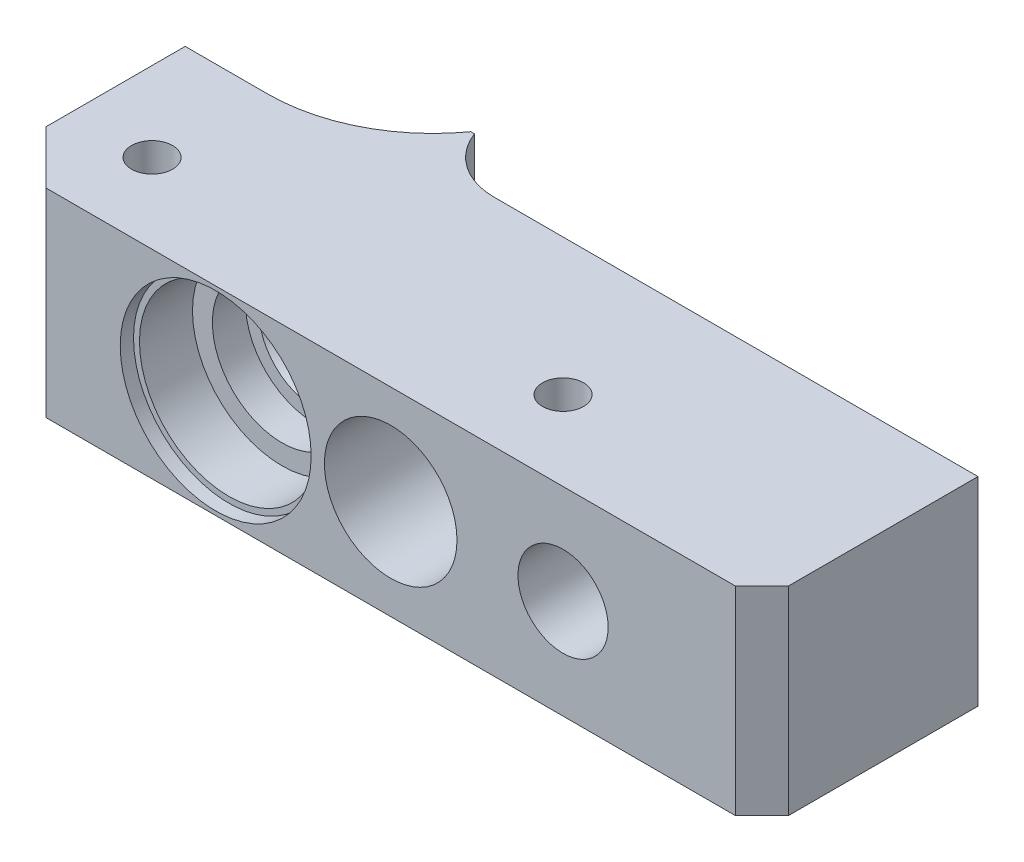
SolidWorks part; units mm, degrees
material "Al-2030"
ref_plane "Alzado" through (0, 0, 0) normal (0, 0, 1) x (1, 0, 0)
ref_plane "Planta" through (0, 0, 0) normal (0, 1, 0) x (1, 0, 0)
ref_plane "Vista lateral" through (0, 0, 0) normal (1, 0, 0) x (0, 0, -1)
sketch "Croquis1" plane through (0, 0, 0) normal (0, 1, 0) x (1, 0, 0)
  line L1 (-37, -6) -> (21, -6)
  line L2 (-37, -6) -> (-37, 6.5)
  line L3 (-37, 6.5) -> (21, 6.5)
  line L7 (21, 6.5) -> (21, -6)
  circle A0 centre (0, 0) radius 1.55
  circle A1 centre (-31, 0) radius 1.55
  dimension "D1" = 3.1
  dimension "D5" = 6
  dimension "D2" = 31
  dimension "D3" = 58
  dimension "D4" = 37
  dimension "D6" = 6.5
extrude "Saliente-Extruir1" add sketch "Croquis1" along normal blind 15
ref_plane "Plano1" through (0, 7.5, 0) normal (0, -1, 0) x (-1, 0, 0)
sketch "Croquis5" plane through (0, 0, 0) normal (0, 1, 0) x (1, 0, 0)
  line L0 (-20.2, -6) -> (-20.2, 16.0649) construction
  line L1 (-37, -6) -> (21, -6) construction
  line L2 (21, 6.5) -> (21, 10.3)
  line L3 (-20.3785, 13.7) -> (-20.6531, 13.7)
  line L4 (21, 6.5) -> (-37, 6.5)
  line L5 (-37, -6) -> (21, -6) construction
  line L6 (21, 6.5) -> (-37, 6.5) construction
  line L7 (-30.8, 8.5) -> (-37, 8.5)
  line L8 (-37, 6.5) -> (-37, 8.5)
  line L9 (-15.5, 10.3) -> (21, 10.3)
  line L10 (21, -6) -> (21, 6.5) construction
  arc A0 (-15.5, 10.3) -> (-20.3785, 13.7) centre (-15.5, 15.5) cw
  circle A2 centre (-31, 0) radius 1.55 construction
  arc A3 (-20.6531, 13.7) -> (-30.8, 8.5) centre (-30.8, 21) cw
  dimension "D3" = 14.5
  dimension "D4" = 10.6
  dimension "D9" = 10.4
  dimension "D11" = 12.5
  dimension "D1" = 10.8
  dimension "D6" = 13.7
  dimension "D7" = 15.5
  dimension "D8" = 15.5
extrude "Saliente-Extruir2" add sketch "Croquis5" along normal up to surface (15 mm away) up to face at (0, 15, 1.55)
sketch "Croquis2" plane through (0, 0, 6) normal (0, 0, 1) x (1, 0, 0)
  line L0 (-37, 15) -> (-37, 0) construction
  line L1 (-31, 15) -> (-31, -5.2235) construction
  line L2 (-37, 7.5) -> (-20.2, 7.5) construction
  line L3 (-29.45, 15) -> (-32.55, 15) construction
  circle A0 centre (-20.2, 7.5) radius 2
  dimension "D1" = 4
  dimension "D2" = 10.8
  dimension "D3" = 16.8
extrude "Cortar-Extruir1" cut sketch "Croquis2" against normal through all
sketch "Croquis24" plane through (0, 0, 6) normal (0, 0, 1) x (1, 0, 0)
  circle A0 centre (-20.2, 7.5) radius 6.75
  dimension "D1" = 13.5
extrude "Cortar-Extruir10" cut sketch "Croquis24" against normal blind 5
sketch "Croquis25" plane through (0, 0, 1) normal (0, 0, 1) x (1, 0, 0)
  circle A0 centre (-20.2, 7.5) radius 5.25
  dimension "D1" = 10.5
extrude "Cortar-Extruir11" cut sketch "Croquis25" against normal blind 2.5
sketch "Croquis26" plane through (0, 0, -1.5) normal (0, 0, 1) x (1, 0, 0)
  circle A0 centre (-20.2, 7.5) radius 3.25
  dimension "D1" = 6.5
extrude "Cortar-Extruir12" cut sketch "Croquis26" against normal blind 7.5
hole_wizard "Taladro roscado M81" positions "Croquis29" profile "Croquis28" tap size "M8" standard "ISO" end condition through all
sketch "Croquis29" plane through (0, 0, 6) normal (0, 0, 1) x (1, 0, 0)
  line L0 (-20.2, 7.5) -> (6, 7.5) construction
  line L1 (-31, 15) -> (-31, -29.4543) construction
  line L3 (-29.45, 15) -> (-32.55, 15) construction
  point P0 (6, 7.5)
  dimension "D1" = 37
sketch "Croquis28" plane through (6, 7.5, 6) normal (1, 0, 0) x (0, -1, 0)
  line L0 (0, 0) -> (0, 19.7)
  line L1 (0, 19.7) -> (3.4, 19.7)
  line L2 (3.4, 19.7) -> (3.4, 0)
  line L5 (3.4, 0) -> (0, 0)
  line L11 (0, -6.35) -> (0, 107.95) construction
  dimension "Diámetro de perforador para roscar hasta el siguiente" = 6.8
  dimension "Profundidad de perforador para roscar hasta el siguiente" = 19.7
cosmetic thread "Rosca de taladro1" parameters "D2"=8
chamfer "Chaflán1" distance 4 angle 45 1 edges at (-37, 7.5, 6)
chamfer "Chaflán2" distance 2 angle 45 1 edges at (21, 7.5, 6)
sketch "Croquis34" plane through (0, 0, 6) normal (0, 0, 1) x (1, 0, 0)
  line L0 (-37, 7.5) -> (-7, 7.5) construction
  line L1 (-37, 0) -> (-37, 15) construction
  circle A0 centre (-7, 7.5) radius 5
  dimension "D2" = 10
  dimension "D1" = 30
extrude "Cortar-Extruir13" cut sketch "Croquis34" against normal through all
chamfer "Chaflán3" distance 1 angle 60 1 edges at (-16.95, 7.5, -1.5)
sketch "Croquis35" plane through (0, 0, 6) normal (0, 0, 1) x (1, 0, 0)
  circle A0 centre (-20.2, 7.5) radius 7.2
  dimension "D1" = 14.4
extrude "Cortar-Extruir14" cut sketch "Croquis35" against normal blind 1
